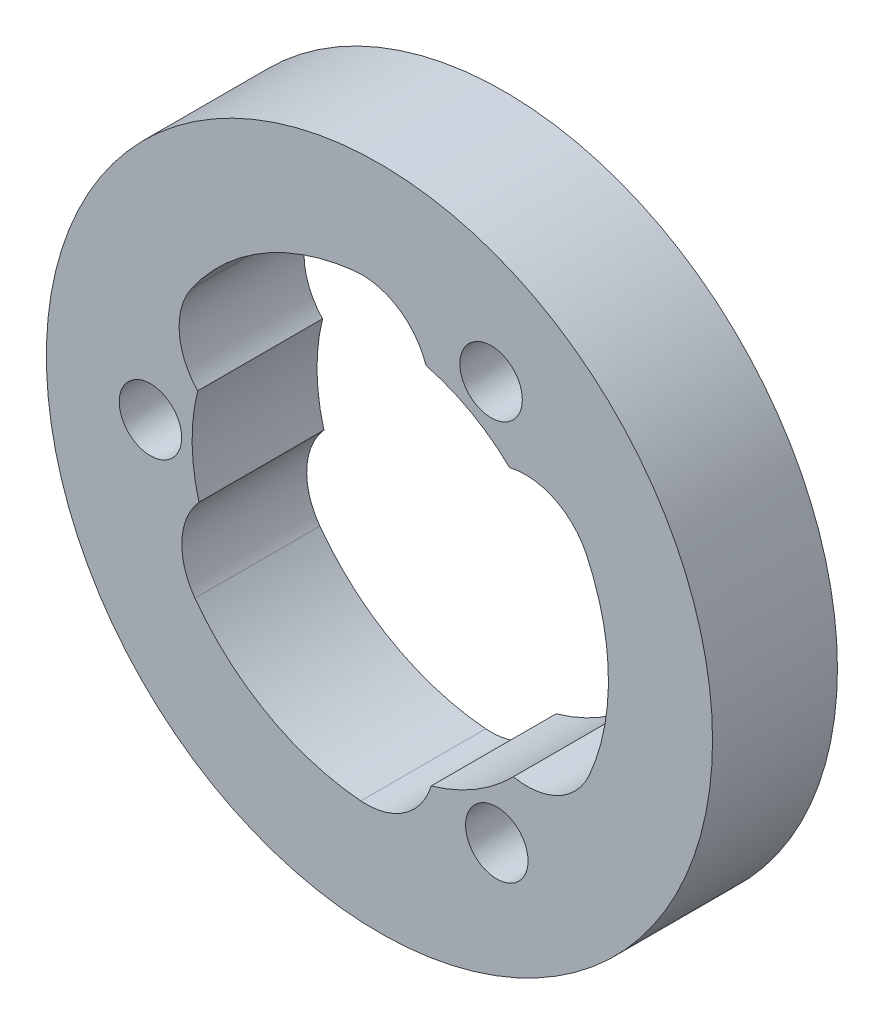
SolidWorks part; units mm, degrees
ref_plane "Plan de face" through (0, 0, 0) normal (0, 0, 1) x (1, 0, 0)
ref_plane "Plan de dessus" through (0, 0, 0) normal (0, 1, 0) x (1, 0, 0)
ref_plane "Plan de droite" through (0, 0, 0) normal (1, 0, 0) x (0, 0, -1)
sketch "Esquisse1" plane through (0, 0, 0) normal (0, 0, 1) x (1, 0, 0)
  line L0 (5.3623, 9.6045) -> (0, 0) construction
  line L1 (-10.9989, -0.1583) -> (5.3623, 9.6045) construction
  line L2 (5.3623, 9.6045) -> (5.6365, -9.4461) construction
  line L3 (5.6365, -9.4461) -> (-10.9989, -0.1583) construction
  circle A0 centre (0, 0) radius 16
  circle A3 centre (-10.9989, -0.1583) radius 1.5
  arc A4 (-8.6673, -2.4245) -> (-8.8628, -6.5154) centre (-6.2442, -4.5904) ccw
  arc A5 (-9.0466, 6.2577) -> (-8.7335, 2.174) centre (-6.3738, 4.4088) ccw
  arc A6 (-8.8628, -6.5154) -> (-0.896, -10.9635) centre (0, 0) ccw
  arc A7 (-8.7339, 2.1724) -> (-8.6677, -2.4229) centre (-10.9989, -0.1583) ccw construction
  arc A8 (6.2483, 6.4775) -> (2.2356, 8.7179) centre (5.3623, 9.6045) ccw construction
  circle A9 centre (5.3623, 9.6045) radius 1.5
  arc A10 (9.9426, 4.7058) -> (6.2495, 6.4764) centre (7.005, 3.3154) ccw
  arc A12 (2.234, 8.7183) -> (-1.2111, 10.9331) centre (-0.8533, 7.7029) ccw
  arc A13 (2.4856, -8.65) -> (6.4322, -6.295) centre (5.6365, -9.4461) ccw construction
  circle A14 centre (5.6365, -9.4461) radius 1.5
  arc A15 (-0.896, -10.9635) -> (2.484, -8.6504) centre (-0.6312, -7.7242) ccw
  arc A17 (6.4333, -6.2939) -> (10.0739, -4.4177) centre (7.0975, -3.1125) ccw
  arc A18 (10.0739, -4.4177) -> (9.9426, 4.7058) centre (0, 0) ccw
  circle A19 centre (0, 0) radius 7.75 construction
  arc A20 (-1.2111, 10.9331) -> (-9.0466, 6.2577) centre (0, 0) ccw
  arc A21 (2.484, -8.6504) -> (6.4333, -6.2939) centre (0, 0) ccw
  arc A23 (6.2495, 6.4764) -> (2.234, 8.7183) centre (0, 0) ccw
  arc A24 (-8.7335, 2.174) -> (-8.6673, -2.4245) centre (0, 0) ccw
  point P32 (0, 0)
  dimension "D1" = 32
  dimension "D2" = 6.5
  dimension "D3" = 3
  dimension "D4" = 3
  dimension "D5" = 15.5
  dimension "D7" = 18
  dimension "D9" = 11
  dimension "D10" = 3.25
  dimension "D11" = 3.25
  dimension "D12" = 7.75
  dimension "D14" = 11
  dimension "D6" = 11
  dimension "D8" = 19.0506
  dimension "D13" = 7.75
extrude "Boss.-Extru.1" add sketch "Esquisse1" along normal blind 6
